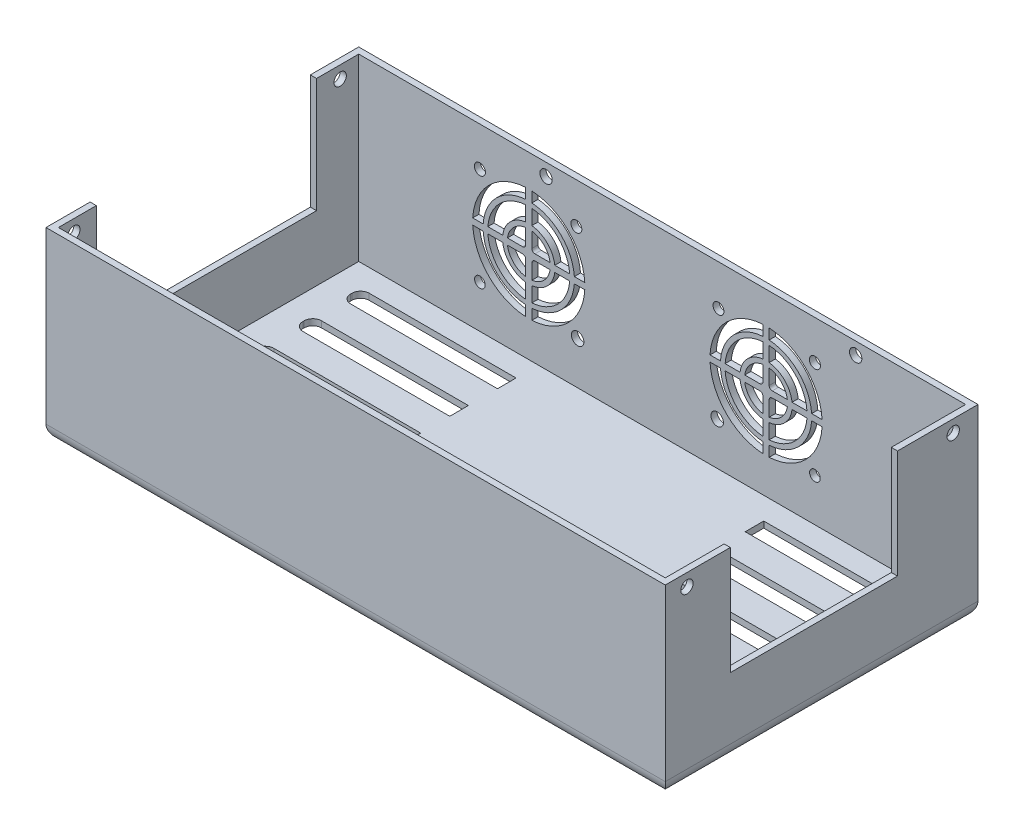
SolidWorks part; units mm, degrees
ref_plane "Alzado" through (0, 0, 0) normal (0, 0, 1) x (1, 0, 0)
ref_plane "Planta" through (0, 0, 0) normal (0, 1, 0) x (1, 0, 0)
ref_plane "Vista lateral" through (0, 0, 0) normal (1, 0, 0) x (0, 0, -1)
sketch "Croquis1" plane through (0, 0, 0) normal (0, 1, 0) x (1, 0, 0)
  line L1 (-100, -50.5) -> (100, -50.5)
  line L2 (-100, -50.5) -> (-100, 50.5)
  line L3 (-100, 50.5) -> (100, 50.5)
  line L4 (100, -50.5) -> (100, 50.5)
  line L5 (-100, -50.5) -> (100, 50.5) construction
  line L6 (-100, 50.5) -> (100, -50.5) construction
  point P0 (0, 0)
  dimension "D1" = 200
  dimension "D2" = 101
extrude "Saliente-Extruir1" add sketch "Croquis1" along normal blind 60
shell "Vaciado1" thickness 2
fillet "Redondeo3" radius 5 4 edges at (-100, 0, 0) (0, 0, 50.5) (100, 0, 0) (0, 0, -50.5)
sketch "Croquis3" plane through (100, 0, 0) normal (1, 0, 0) x (0, 0, -1)
  line L0 (-43.5, 60) -> (-43.5, 56) construction
  line L1 (-50.5, 60) -> (50.5, 60) construction
  line L2 (-43.5, 56) -> (-50.5, 56) construction
  line L3 (-50.5, 60) -> (-50.5, 5) construction
  line L4 (50.5, 56) -> (42.5, 56) construction
  line L5 (50.5, 60) -> (50.5, 5) construction
  line L6 (42.5, 56) -> (42.5, 60) construction
  circle A0 centre (-43.5, 56) radius 2
  circle A1 centre (42.5, 56) radius 2
  dimension "D3" = 8
  dimension "D1" = 4
  dimension "D2" = 7
extrude "Cortar-Extruir1" cut sketch "Croquis3" against normal blind 220
sketch "Croquis5" plane through (0, 0, -50.5) normal (0, 0, -1) x (-1, 0, 0)
  line L0 (-100, 56) -> (100, 56) construction
  line L1 (-100, 60) -> (-100, 5) construction
  line L2 (100, 60) -> (100, 5) construction
  line L3 (-100, 60) -> (100, 60) construction
  line L4 (-62.5, 60) -> (-62.5, 56) construction
  line L5 (37.5, 60) -> (37.5, 56) construction
  circle A0 centre (-62.5, 56) radius 2
  circle A1 centre (37.5, 56) radius 2
  dimension "D1" = 4
  dimension "D2" = 37.5
  dimension "D3" = 2
extrude "Cortar-Extruir3" cut sketch "Croquis5" against normal blind 10
sketch "Croquis7" plane through (0, 0, -50.5) normal (0, 0, -1) x (-1, 0, 0)
  line L1 (-53.5477, 11.5867) -> (-13.5477, 11.5867) construction
  line L2 (-53.5477, 11.5867) -> (-53.5477, 51.5867) construction
  line L3 (-53.5477, 51.5867) -> (-13.5477, 51.5867) construction
  line L4 (-13.5477, 11.5867) -> (-13.5477, 51.5867) construction
  line L5 (-53.5477, 11.5867) -> (-13.5477, 51.5867) construction
  line L6 (-53.5477, 51.5867) -> (-13.5477, 11.5867) construction
  point P0 (-33.5477, 31.5867)
  dimension "D1" = 40
  dimension "D2" = 40
sketch "Croquis8" plane through (0, 0, -50.5) normal (0, 0, -1) x (-1, 0, 0)
  line L0 (-53.5477, 11.5867) -> (-13.5477, 51.5867) construction
  line L1 (-53.5477, 51.5867) -> (-13.5477, 11.5867) construction
  line L2 (-46.7651, 32.5867) -> (-41.946, 32.5867)
  line L3 (4.7702, 60) -> (4.7702, 5) construction
  line L4 (-100, 60) -> (100, 60) construction
  line L5 (-100, 5) -> (100, 5) construction
  line L6 (56.3055, 30.5867) -> (51.4864, 30.5867)
  line L7 (42.0881, 16.8654) -> (42.0881, 13.4912)
  line L8 (-34.5477, 49.6823) -> (-34.5477, 46.3081)
  line L9 (-32.5477, 49.6823) -> (-32.5477, 46.3081)
  line L10 (-51.6432, 32.5867) -> (-48.269, 32.5867)
  line L11 (-51.6432, 30.5867) -> (-48.269, 30.5867)
  line L12 (-34.5477, 29.5867) -> (-34.5477, 24.7013)
  line L13 (-31.5477, 32.5867) -> (-26.6623, 32.5867)
  line L14 (44.0881, 16.8654) -> (44.0881, 13.4912)
  line L15 (-32.5477, 29.5867) -> (-32.5477, 24.7013)
  line L16 (-31.5477, 30.5867) -> (-26.6623, 30.5867)
  line L17 (-34.5477, 44.8042) -> (-34.5477, 39.9851)
  line L18 (-32.5477, 44.8042) -> (-32.5477, 39.9851)
  line L19 (-18.8264, 32.5867) -> (-15.4521, 32.5867)
  line L20 (-18.8264, 30.5867) -> (-15.4521, 30.5867)
  line L21 (-25.1493, 32.5867) -> (-20.3302, 32.5867)
  line L22 (-25.1493, 30.5867) -> (-20.3302, 30.5867)
  line L23 (-34.5477, 23.1884) -> (-34.5477, 18.3693)
  line L24 (-32.5477, 23.1884) -> (-32.5477, 18.3693)
  line L25 (-40.4331, 32.5867) -> (-35.5477, 32.5867)
  line L26 (-40.4331, 30.5867) -> (-35.5477, 30.5867)
  line L27 (-34.5477, 38.4721) -> (-34.5477, 33.5867)
  line L28 (-32.5477, 38.4721) -> (-32.5477, 33.5867)
  line L29 (-34.5477, 16.8654) -> (-34.5477, 13.4912)
  line L30 (-32.5477, 16.8654) -> (-32.5477, 13.4912)
  line L31 (-46.7651, 30.5867) -> (-41.946, 30.5867)
  line L32 (42.0881, 38.4721) -> (42.0881, 33.5867)
  line L33 (44.0881, 38.4721) -> (44.0881, 33.5867)
  line L34 (49.9735, 30.5867) -> (45.0881, 30.5867)
  line L35 (49.9735, 32.5867) -> (45.0881, 32.5867)
  line L36 (42.0881, 23.1884) -> (42.0881, 18.3693)
  line L37 (44.0881, 23.1884) -> (44.0881, 18.3693)
  line L38 (34.6898, 30.5867) -> (29.8706, 30.5867)
  line L39 (34.6898, 32.5867) -> (29.8706, 32.5867)
  line L40 (28.3668, 30.5867) -> (24.9925, 30.5867)
  line L41 (28.3668, 32.5867) -> (24.9925, 32.5867)
  line L42 (42.0881, 44.8042) -> (42.0881, 39.9851)
  line L43 (44.0881, 44.8042) -> (44.0881, 39.9851)
  line L44 (41.0881, 30.5867) -> (36.2027, 30.5867)
  line L45 (42.0881, 29.5867) -> (42.0881, 24.7013)
  line L46 (41.0881, 32.5867) -> (36.2027, 32.5867)
  line L47 (44.0881, 29.5867) -> (44.0881, 24.7013)
  line L48 (61.1836, 30.5867) -> (57.8094, 30.5867)
  line L49 (61.1836, 32.5867) -> (57.8094, 32.5867)
  line L50 (42.0881, 49.6823) -> (42.0881, 46.3081)
  line L51 (44.0881, 49.6823) -> (44.0881, 46.3081)
  line L52 (56.3055, 32.5867) -> (51.4864, 32.5867)
  arc A0 (-51.6432, 30.5867) -> (-34.5477, 13.4912) centre (-33.5477, 31.5867) ccw
  circle A1 centre (-18.1788, 46.9556) radius 1.7627
  circle A2 centre (-49.3352, 15.7992) radius 1.7191
  circle A3 centre (-49.3352, 47.3743) radius 1.7931
  circle A4 centre (-17.7602, 15.7992) radius 2.0244
  arc A5 (-34.5477, 29.5867) -> (-35.5477, 30.5867) centre (-35.5477, 29.5867) ccw
  arc A6 (-32.5477, 29.5867) -> (-31.5477, 30.5867) centre (-31.5477, 29.5867) cw
  arc A7 (-31.5477, 32.5867) -> (-32.5477, 33.5867) centre (-31.5477, 33.5867) cw
  arc A8 (-34.5477, 33.5867) -> (-35.5477, 32.5867) centre (-35.5477, 33.5867) cw
  arc A9 (-40.4331, 30.5867) -> (-34.5477, 24.7013) centre (-33.5477, 31.5867) ccw
  arc A10 (-41.946, 30.5867) -> (-34.5477, 23.1884) centre (-33.5477, 31.5867) ccw
  arc A11 (-46.7651, 30.5867) -> (-34.5477, 18.3693) centre (-33.5477, 31.5867) ccw
  arc A12 (-48.269, 30.5867) -> (-34.5477, 16.8654) centre (-33.5477, 31.5867) ccw
  arc A13 (-26.6623, 32.5867) -> (-32.5477, 38.4721) centre (-33.5477, 31.5867) ccw
  arc A14 (-25.1493, 32.5867) -> (-32.5477, 39.9851) centre (-33.5477, 31.5867) ccw
  arc A15 (-20.3302, 32.5867) -> (-32.5477, 44.8042) centre (-33.5477, 31.5867) ccw
  arc A16 (-18.8264, 32.5867) -> (-32.5477, 46.3081) centre (-33.5477, 31.5867) ccw
  arc A17 (-15.4521, 32.5867) -> (-32.5477, 49.6823) centre (-33.5477, 31.5867) ccw
  arc A18 (-34.5477, 49.6823) -> (-51.6432, 32.5867) centre (-33.5477, 31.5867) ccw
  arc A19 (-34.5477, 46.3081) -> (-48.269, 32.5867) centre (-33.5477, 31.5867) ccw
  arc A20 (-34.5477, 44.8042) -> (-46.7651, 32.5867) centre (-33.5477, 31.5867) ccw
  arc A21 (-34.5477, 39.9851) -> (-41.946, 32.5867) centre (-33.5477, 31.5867) ccw
  arc A22 (-34.5477, 38.4721) -> (-40.4331, 32.5867) centre (-33.5477, 31.5867) ccw
  arc A23 (-32.5477, 24.7013) -> (-26.6623, 30.5867) centre (-33.5477, 31.5867) ccw
  arc A24 (-32.5477, 23.1884) -> (-25.1493, 30.5867) centre (-33.5477, 31.5867) ccw
  arc A25 (-32.5477, 18.3693) -> (-20.3302, 30.5867) centre (-33.5477, 31.5867) ccw
  arc A26 (-32.5477, 16.8654) -> (-18.8264, 30.5867) centre (-33.5477, 31.5867) ccw
  arc A27 (-32.5477, 13.4912) -> (-15.4521, 30.5867) centre (-33.5477, 31.5867) ccw
  arc A28 (42.0881, 13.4912) -> (24.9925, 30.5867) centre (43.0881, 31.5867) cw
  arc A29 (42.0881, 16.8654) -> (28.3668, 30.5867) centre (43.0881, 31.5867) cw
  arc A30 (42.0881, 18.3693) -> (29.8706, 30.5867) centre (43.0881, 31.5867) cw
  arc A31 (42.0881, 23.1884) -> (34.6898, 30.5867) centre (43.0881, 31.5867) cw
  arc A32 (42.0881, 24.7013) -> (36.2027, 30.5867) centre (43.0881, 31.5867) cw
  arc A33 (44.0881, 38.4721) -> (49.9735, 32.5867) centre (43.0881, 31.5867) cw
  arc A34 (44.0881, 39.9851) -> (51.4864, 32.5867) centre (43.0881, 31.5867) cw
  arc A35 (44.0881, 44.8042) -> (56.3055, 32.5867) centre (43.0881, 31.5867) cw
  arc A36 (44.0881, 46.3081) -> (57.8094, 32.5867) centre (43.0881, 31.5867) cw
  arc A37 (44.0881, 49.6823) -> (61.1836, 32.5867) centre (43.0881, 31.5867) cw
  arc A38 (24.9925, 32.5867) -> (42.0881, 49.6823) centre (43.0881, 31.5867) cw
  arc A39 (28.3668, 32.5867) -> (42.0881, 46.3081) centre (43.0881, 31.5867) cw
  arc A40 (29.8706, 32.5867) -> (42.0881, 44.8042) centre (43.0881, 31.5867) cw
  arc A41 (34.6898, 32.5867) -> (42.0881, 39.9851) centre (43.0881, 31.5867) cw
  arc A42 (36.2027, 32.5867) -> (42.0881, 38.4721) centre (43.0881, 31.5867) cw
  arc A43 (57.8094, 30.5867) -> (44.0881, 16.8654) centre (43.0881, 31.5867) cw
  arc A44 (56.3055, 30.5867) -> (44.0881, 18.3693) centre (43.0881, 31.5867) cw
  arc A45 (51.4864, 30.5867) -> (44.0881, 23.1884) centre (43.0881, 31.5867) cw
  arc A46 (49.9735, 30.5867) -> (44.0881, 24.7013) centre (43.0881, 31.5867) cw
  arc A47 (44.0881, 33.5867) -> (45.0881, 32.5867) centre (45.0881, 33.5867) ccw
  arc A48 (41.0881, 32.5867) -> (42.0881, 33.5867) centre (41.0881, 33.5867) ccw
  arc A49 (42.0881, 29.5867) -> (41.0881, 30.5867) centre (41.0881, 29.5867) ccw
  arc A50 (44.0881, 29.5867) -> (45.0881, 30.5867) centre (45.0881, 29.5867) cw
  circle A51 centre (27.3006, 15.7992) radius 2.0244
  circle A52 centre (58.8756, 47.3743) radius 1.7931
  circle A53 centre (58.8756, 15.7992) radius 1.7191
  circle A54 centre (27.7192, 46.9556) radius 1.7627
  arc A55 (61.1836, 30.5867) -> (44.0881, 13.4912) centre (43.0881, 31.5867) cw
  point P30 (-32.5477, 30.5867)
  point P134 (42.0881, 30.5867)
  dimension "D1" = 1
  dimension "D2" = 1.5
  dimension "D3" = 1.5
extrude "Cortar-Extruir4" cut sketch "Croquis8" against normal blind 10
sketch "Croquis9" plane through (100, 0, 0) normal (1, 0, 0) x (0, 0, -1)
  line L0 (-50.5, 60) -> (50.5, 60) construction
  line L1 (-29.5, 60) -> (24.5, 60)
  line L2 (-29.5, 60) -> (-29.5, 25)
  line L3 (-29.5, 25) -> (24.5, 25)
  line L4 (24.5, 60) -> (24.5, 25)
  line L5 (50.5, 60) -> (50.5, 5) construction
  line L6 (-36.5, 60) -> (39.5, 60) construction
  line L7 (-36.5, 60) -> (-36.5, 20) construction
  line L8 (-36.5, 20) -> (39.5, 20) construction
  line L9 (39.5, 60) -> (39.5, 20) construction
  dimension "D1" = 54
  dimension "D2" = 76
  dimension "D3" = 11
  dimension "D4" = 15
  dimension "D5" = 35
  dimension "D6" = 40
extrude "Cortar-Extruir5" cut sketch "Croquis9" against normal blind 10
sketch "Croquis10" plane through (-100, 0, 0) normal (-1, 0, 0) x (0, 0, 1)
  line L0 (-50.5, 60) -> (50.5, 60) construction
  line L1 (-34.8736, 60) -> (36.2495, 60)
  line L2 (-34.8736, 60) -> (-34.8736, 23.0147)
  line L3 (-34.8736, 23.0147) -> (36.2495, 23.0147)
  line L4 (36.2495, 60) -> (36.2495, 23.0147)
extrude "Cortar-Extruir6" cut sketch "Croquis10" against normal blind 10
sketch "Croquis11" plane through (0, 0, 0) normal (0, -1, 0) x (1, 0, 0)
  line L0 (-87.4242, 26.3037) -> (-40, 26.3037)
  line L1 (40, 10.9009) -> (87.4242, 10.9009)
  line L2 (90.2242, -41.7064) -> (90.2242, 41.7064) construction
  line L3 (90.2242, 41.7064) -> (40, 41.7064) construction
  line L4 (-90.2242, -41.7064) -> (-90.2242, 41.7064) construction
  line L5 (90.2242, -41.7064) -> (43.0598, -19.9045) construction
  line L6 (90.2242, 41.7064) -> (43.9233, 20.3037) construction
  line L7 (-87.4242, 41.7064) -> (-40, 41.7064)
  line L8 (-90.2242, 38.9064) -> (-90.2242, 38.5064)
  line L9 (-87.4242, 35.7064) -> (-40, 35.7064)
  line L10 (90.2242, 38.9064) -> (90.2242, 38.5064)
  line L11 (-87.4242, 20.3037) -> (-40, 20.3037)
  line L12 (90.2242, 23.5037) -> (90.2242, 23.1037)
  line L13 (-90.2242, 23.5037) -> (-90.2242, 23.1037)
  line L14 (-87.4242, 10.9009) -> (-40, 10.9009)
  line L15 (-87.4242, 4.9009) -> (-40, 4.9009)
  line L16 (90.2242, 8.1009) -> (90.2242, 7.7009)
  line L17 (-90.2242, 8.1009) -> (-90.2242, 7.7009)
  line L18 (-87.4242, -4.5018) -> (-40, -4.5018)
  line L19 (-87.4242, -10.5018) -> (-40, -10.5018)
  line L20 (90.2242, -7.3018) -> (90.2242, -7.7018)
  line L21 (-90.2242, -7.3018) -> (-90.2242, -7.7018)
  line L22 (-87.4242, -19.9045) -> (-40, -19.9045)
  line L23 (-87.4242, -25.9045) -> (-40, -25.9045)
  line L24 (90.2242, -22.7045) -> (90.2242, -23.1045)
  line L25 (-90.2242, -22.7045) -> (-90.2242, -23.1045)
  line L26 (-87.4242, -35.3072) -> (-40, -35.3072)
  line L27 (-87.4242, -41.3072) -> (-40, -41.3072)
  line L28 (90.2242, -38.1072) -> (90.2242, -38.5072)
  line L29 (-90.2242, -38.1072) -> (-90.2242, -38.5072)
  line L30 (40, 41.7064) -> (40, 35.7064)
  line L31 (0, 41.7064) -> (0, -41.3072) construction
  line L32 (-40, 41.7064) -> (-40, 35.7064)
  line L33 (-40, 41.7064) -> (-90.2242, 41.7064) construction
  line L34 (40, 41.7064) -> (87.4242, 41.7064)
  line L35 (40, 35.7064) -> (87.4242, 35.7064)
  line L36 (40, 26.3037) -> (87.4242, 26.3037)
  line L37 (40, 20.3037) -> (87.4242, 20.3037)
  line L38 (-43.9233, 20.3037) -> (-90.2242, 41.7064) construction
  line L39 (-40, 26.3037) -> (-40, 20.3037)
  line L40 (-40, 10.9009) -> (-40, 4.9009)
  line L41 (-40, -4.5018) -> (-40, -10.5018)
  line L42 (-40, -19.9045) -> (-40, -25.9045)
  line L43 (-43.0598, -19.9045) -> (-90.2242, -41.7064) construction
  line L44 (40, -19.9045) -> (87.4242, -19.9045)
  line L45 (40, -25.9045) -> (87.4242, -25.9045)
  line L46 (40, -35.3072) -> (87.4242, -35.3072)
  line L47 (40, -41.3072) -> (87.4242, -41.3072)
  line L48 (-40, -35.3072) -> (-40, -41.3072)
  line L49 (40, 4.9009) -> (87.4242, 4.9009)
  line L50 (40, -4.5018) -> (87.4242, -4.5018)
  line L51 (40, 26.3037) -> (40, 20.3037)
  line L52 (40, -10.5018) -> (87.4242, -10.5018)
  line L53 (40, 10.9009) -> (40, 4.9009)
  line L54 (40, -4.5018) -> (40, -10.5018)
  line L55 (40, -19.9045) -> (40, -25.9045)
  line L56 (40, -35.3072) -> (40, -41.3072)
  arc A0 (87.4242, 35.7064) -> (90.2242, 38.5064) centre (87.4242, 38.5064) ccw
  arc A1 (87.4242, 41.7064) -> (90.2242, 38.9064) centre (87.4242, 38.9064) cw
  arc A2 (-90.2242, 38.5064) -> (-87.4242, 35.7064) centre (-87.4242, 38.5064) ccw
  arc A3 (-87.4242, 41.7064) -> (-90.2242, 38.9064) centre (-87.4242, 38.9064) ccw
  arc A4 (87.4242, 26.3037) -> (90.2242, 23.5037) centre (87.4242, 23.5037) cw
  arc A5 (87.4242, 20.3037) -> (90.2242, 23.1037) centre (87.4242, 23.1037) ccw
  arc A6 (-87.4242, 26.3037) -> (-90.2242, 23.5037) centre (-87.4242, 23.5037) ccw
  arc A7 (-90.2242, 23.1037) -> (-87.4242, 20.3037) centre (-87.4242, 23.1037) ccw
  arc A8 (87.4242, 10.9009) -> (90.2242, 8.1009) centre (87.4242, 8.1009) cw
  arc A9 (87.4242, 4.9009) -> (90.2242, 7.7009) centre (87.4242, 7.7009) ccw
  arc A10 (-87.4242, 10.9009) -> (-90.2242, 8.1009) centre (-87.4242, 8.1009) ccw
  arc A11 (-90.2242, 7.7009) -> (-87.4242, 4.9009) centre (-87.4242, 7.7009) ccw
  arc A12 (87.4242, -4.5018) -> (90.2242, -7.3018) centre (87.4242, -7.3018) cw
  arc A13 (87.4242, -10.5018) -> (90.2242, -7.7018) centre (87.4242, -7.7018) ccw
  arc A14 (-87.4242, -4.5018) -> (-90.2242, -7.3018) centre (-87.4242, -7.3018) ccw
  arc A15 (-90.2242, -7.7018) -> (-87.4242, -10.5018) centre (-87.4242, -7.7018) ccw
  arc A16 (87.4242, -19.9045) -> (90.2242, -22.7045) centre (87.4242, -22.7045) cw
  arc A17 (87.4242, -25.9045) -> (90.2242, -23.1045) centre (87.4242, -23.1045) ccw
  arc A18 (-87.4242, -19.9045) -> (-90.2242, -22.7045) centre (-87.4242, -22.7045) ccw
  arc A19 (-90.2242, -23.1045) -> (-87.4242, -25.9045) centre (-87.4242, -23.1045) ccw
  arc A20 (87.4242, -35.3072) -> (90.2242, -38.1072) centre (87.4242, -38.1072) cw
  arc A21 (87.4242, -41.3072) -> (90.2242, -38.5072) centre (87.4242, -38.5072) ccw
  arc A22 (-87.4242, -35.3072) -> (-90.2242, -38.1072) centre (-87.4242, -38.1072) ccw
  arc A23 (-90.2242, -38.5072) -> (-87.4242, -41.3072) centre (-87.4242, -38.5072) ccw
  point P0 (0, 0)
  point P10 (90.2242, 35.7064)
  point P16 (-90.2242, 35.7064)
  dimension "D2" = 2.8
  dimension "D1" = 6
  dimension "D4" = 40
  dimension "D3" = 6
extrude "Cortar-Extruir7" cut sketch "Croquis11" against normal blind 10
